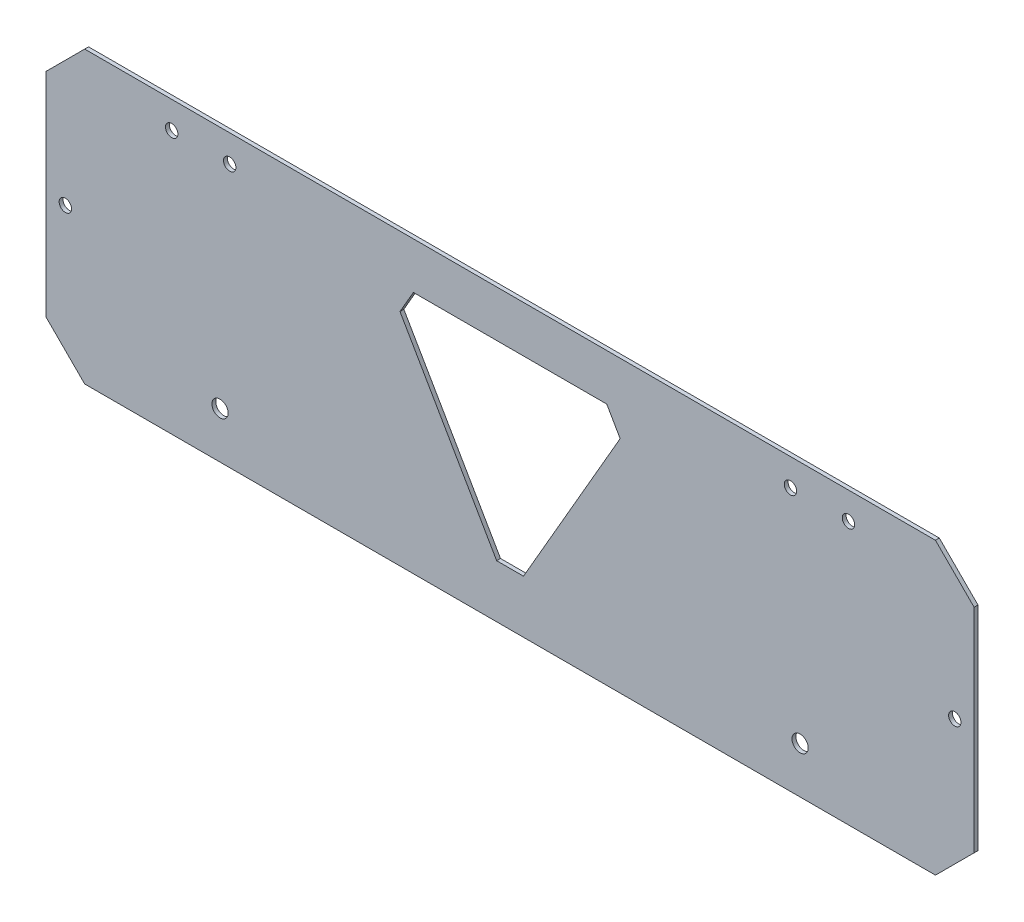
SolidWorks part; units mm, degrees
ref_plane "前视基准面" through (0, 0, 0) normal (0, 0, 1) x (1, 0, 0)
ref_plane "上视基准面" through (0, 0, 0) normal (0, 1, 0) x (1, 0, 0)
ref_plane "右视基准面" through (0, 0, 0) normal (1, 0, 0) x (0, 0, -1)
sketch "草图1" plane through (0, 0, 0) normal (0, 0, 1) x (1, 0, 0)
  line L0 (120, 0) -> (120, -120) construction
  line L1 (0, 0) -> (240, 0)
  line L2 (0, 0) -> (0, 75)
  line L3 (0, 75) -> (240, 75)
  line L4 (240, 0) -> (240, 75)
  line L5 (120, -120) -> (0, 0) construction
  line L6 (120, -120) -> (240, 0) construction
  line L7 (120, 75) -> (120, 0) construction
  dimension "D1" = 240
  dimension "D2" = 75
extrude "凸台-拉伸1" add sketch "草图1" along normal blind 1
chamfer "倒角1" distance 10 angle 45 4 edges at (240, 75, 0.5) (240, 0, 0.5) (0, 0, 0.5) (0, 75, 0.5)
sketch "草图3" plane through (0, 0, 0) normal (0, 0, -1) x (-1, 0, 0)
  line L0 (-120, 0) -> (-120, 75) construction
  line L1 (-10, 0) -> (-230, 0) construction
  line L2 (-230, 75) -> (-10, 75) construction
  line L3 (-135, 33.6603) -> (-148.4697, 56.9904)
  line L4 (-100, 25) -> (-110, 42.3205)
  line L5 (-110, 42.3205) -> (-130, 42.3205)
  line L6 (-130, 42.3205) -> (-140, 25)
  line L7 (-140, 25) -> (-130, 7.6795)
  line L8 (-130, 7.6795) -> (-110, 7.6795)
  line L9 (-110, 7.6795) -> (-100, 25)
  line L10 (-148.4697, 56.9904) -> (-145, 63)
  line L11 (-145, 63) -> (-95, 63)
  line L12 (-105, 33.6603) -> (-91.5303, 56.9904)
  line L13 (-91.5303, 56.9904) -> (-95, 63)
  circle A0 centre (-120, 25) radius 17.3205 construction
  point P22 (-120, 63)
  dimension "D1" = 20
  dimension "D2" = 25
  dimension "D3" = 12
  dimension "D4" = 25
extrude "切除-拉伸2" cut sketch "草图3" against normal blind 10 contours L12 L13 L11 L10 L3 L6 L5 L4 | L8 L9 L4 L5 L6 L7
sketch "草图4" plane through (0, 0, 0) normal (0, 0, -1) x (-1, 0, 0)
  line L0 (-120, 75) -> (-120, 45) construction
  line L1 (-230, 75) -> (-10, 75) construction
  line L2 (-195, 12) -> (-45, 12) construction
  line L3 (-120, 12) -> (-120, 0) construction
  line L4 (-10, 0) -> (-230, 0) construction
  line L5 (-207.5, 68) -> (-192.5, 68) construction
  line L6 (-200, 68) -> (-200, 75) construction
  line L7 (-40, 68) -> (-40, 75) construction
  line L8 (-32.5, 68) -> (-47.5, 68) construction
  line L9 (-235, 37.5) -> (-240, 37.5) construction
  line L10 (-240, 10) -> (-240, 65) construction
  line L11 (-5, 37.5) -> (0, 37.5) construction
  line L12 (0, 65) -> (0, 10) construction
  circle A0 centre (-195, 12) radius 2.1
  circle A1 centre (-45, 12) radius 2.1
  circle A2 centre (-207.5, 68) radius 1.6
  circle A3 centre (-192.5, 68) radius 1.6
  circle A4 centre (-47.5, 68) radius 1.6
  circle A5 centre (-32.5, 68) radius 1.6
  circle A6 centre (-235, 37.5) radius 1.6
  circle A7 centre (-5, 37.5) radius 1.6
  dimension "D2" = 4.2
  dimension "D5" = 3.2
  dimension "D10" = 3.2
  dimension "D12" = 3.2
  dimension "D1" = 30
  dimension "D3" = 12
  dimension "D4" = 150
  dimension "D6" = 7
  dimension "D7" = 80
  dimension "D8" = 15
  dimension "D9" = 5
  dimension "D11" = 5
extrude "切除-拉伸3" cut sketch "草图4" against normal blind 10
sketch "草图5" plane through (0, 0, 1) normal (0, 0, 1) x (1, 0, 0)
  line L0 (135, 33.6603) -> (123.4697, 13.6891)
  line L1 (123.4697, 13.6891) -> (116.5303, 13.6891)
  line L2 (116.5303, 13.6891) -> (105, 33.6603)
  line L3 (105, 33.6603) -> (91.5303, 56.9904) construction
  line L4 (135, 33.6603) -> (148.4697, 56.9904) construction
  line L5 (135, 33.6603) -> (140, 25)
  line L6 (140, 25) -> (130, 7.6795)
  line L7 (130, 7.6795) -> (110, 7.6795)
  line L8 (110, 7.6795) -> (100, 25)
  line L9 (100, 25) -> (105, 33.6603)
  line L10 (100, 25) -> (105, 33.6603) construction
  dimension "D1" = 50
extrude "凸台-拉伸2" add sketch "草图5" against normal blind 1
